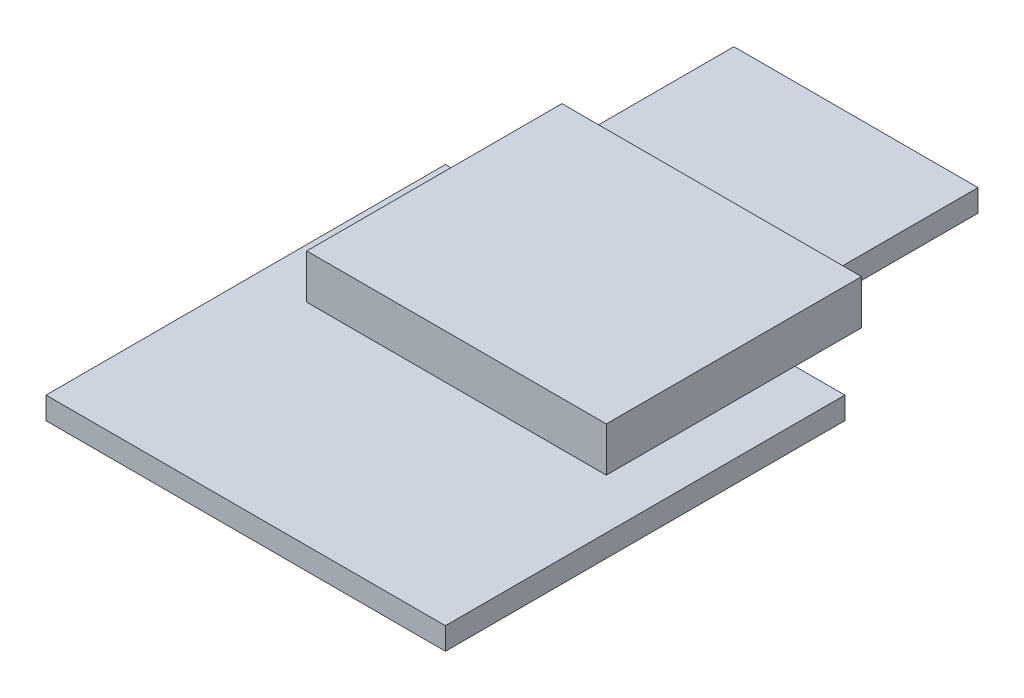
SolidWorks part; units mm, degrees
ref_plane "Front Plane" through (0, 0, 0) normal (0, 0, 1) x (1, 0, 0)
ref_plane "Top Plane" through (0, 0, 0) normal (0, 1, 0) x (1, 0, 0)
ref_plane "Right Plane" through (0, 0, 0) normal (1, 0, 0) x (0, 0, -1)
sketch "Sketch1" plane through (0, 0, 0) normal (0, 1, 0) x (1, 0, 0)
  line L1 (0, 0) -> (18, 0)
  line L2 (0, 0) -> (0, -18)
  line L3 (0, -18) -> (18, -18)
  line L4 (18, 0) -> (18, -18)
  dimension "D1" = 18
extrude "Boss-Extrude1" add sketch "Sketch1" along normal blind 1
sketch "Sketch2" plane through (0, 1, 0) normal (0, 1, 0) x (1, 0, 0)
  line L0 (9, -26.1879) -> (9, 21.3197) construction
  line L1 (2.25, -8.5) -> (15.75, -8.5)
  line L2 (2.25, -8.5) -> (2.25, 3)
  line L3 (2.25, 3) -> (15.75, 3)
  line L4 (15.75, -8.5) -> (15.75, 3)
  line L5 (0, 0) -> (0, -18) construction
  line L6 (18, -18) -> (18, 0) construction
  line L7 (18, 0) -> (0, 0) construction
  dimension "D1" = 13.5
  dimension "D2" = 11.5
  dimension "D3" = 3
extrude "Boss-Extrude2" add sketch "Sketch2" along normal blind 2
sketch "Sketch3" plane through (0, 0, -3) normal (0, 0, -1) x (-1, 0, 0)
  line L0 (-9, 1) -> (-9, 4.9662) construction
  line L1 (-14.5, 2.5968) -> (-3.5, 2.5968)
  line L2 (-14.5, 2.5968) -> (-14.5, 1.5968)
  line L3 (-14.5, 1.5968) -> (-3.5, 1.5968)
  line L4 (-3.5, 2.5968) -> (-3.5, 1.5968)
  line L5 (-15.75, 1) -> (-2.25, 1) construction
  line L6 (-15.75, 3) -> (-2.25, 3) construction
  dimension "D1" = 1
  dimension "D2" = 11
  dimension "D3" = 0.4032
extrude "Boss-Extrude3" add sketch "Sketch3" along normal blind 6.5
ref_plane "Plane1" through (9, 0, 0) normal (1, 0, 0) x (0, 0, -1)
